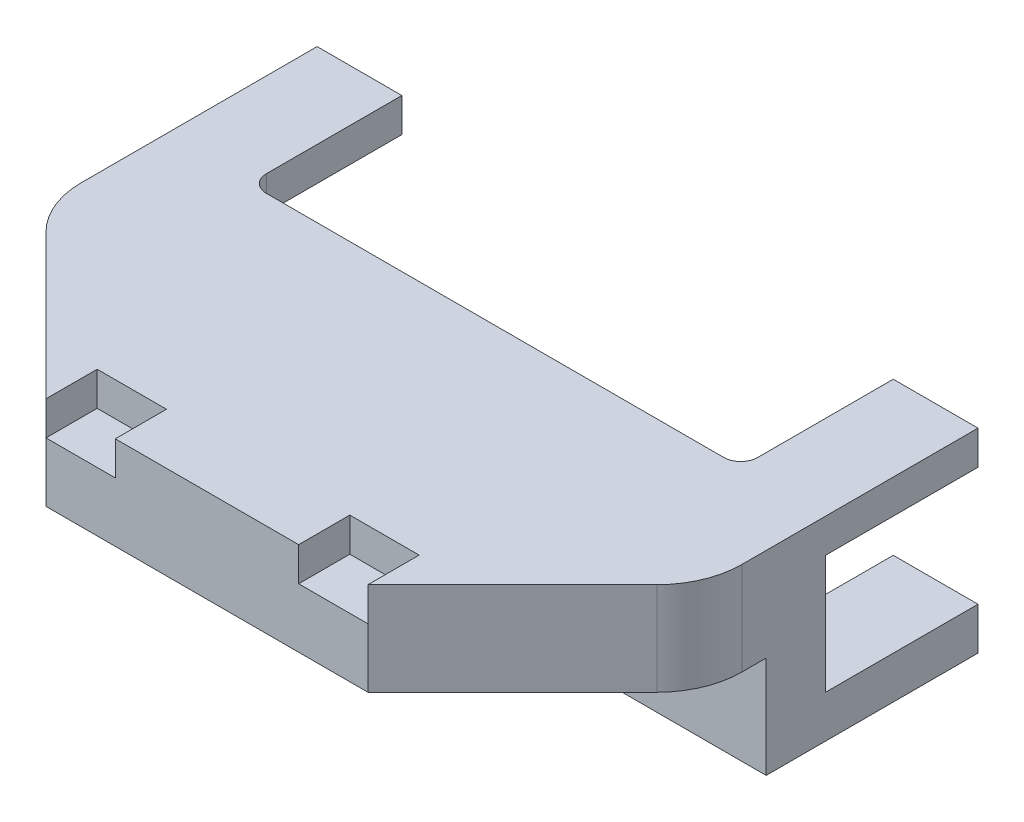
SolidWorks part; units mm, degrees
ref_plane "Front Plane" through (0, 0, 0) normal (0, 0, 1) x (1, 0, 0)
ref_plane "Top Plane" through (0, 0, 0) normal (0, 1, 0) x (1, 0, 0)
ref_plane "Right Plane" through (0, 0, 0) normal (1, 0, 0) x (0, 0, -1)
sketch "Sketch1" plane through (0, 0, 0) normal (0, 0, 1) x (1, 0, 0)
  line L1 (0, 0) -> (39, 0)
  line L2 (0, 0) -> (0, -11.5)
  line L3 (0, -11.5) -> (39, -11.5)
  line L4 (39, 0) -> (39, -11.5)
  dimension "D1" = 11.5
  dimension "D2" = 39
extrude "Boss-Extrude1" add sketch "Sketch1" along normal blind 17
sketch "Sketch2" plane through (0, 0, 0) normal (0, 0, -1) x (-1, 0, 0)
  line L1 (0, -11.5) -> (-5, -11.5)
  line L2 (0, -11.5) -> (0, -9)
  line L3 (0, -9) -> (-5, -9)
  line L4 (-5, -11.5) -> (-5, -9)
  line L5 (0, 0) -> (-5, 0)
  line L6 (0, 0) -> (0, -2)
  line L7 (0, -2) -> (-5, -2)
  line L8 (-5, 0) -> (-5, -2)
  line L9 (-39, -11.5) -> (-34, -11.5)
  line L10 (-39, -11.5) -> (-39, -9)
  line L11 (-39, -9) -> (-34, -9)
  line L12 (-34, -11.5) -> (-34, -9)
  line L13 (-39, 0) -> (-34, 0)
  line L14 (-39, 0) -> (-39, -2)
  line L15 (-39, -2) -> (-34, -2)
  line L16 (-34, 0) -> (-34, -2)
  dimension "D1" = 2.5
  dimension "D2" = 2
  dimension "D3" = 2.5
  dimension "D4" = 2
  dimension "D5" = 5
  dimension "D6" = 5
  dimension "D7" = 5
  dimension "D8" = 5
extrude "Boss-Extrude2" add sketch "Sketch2" along normal blind 9
fillet "Fillet3" radius 1 1 edges at (34, -1, 0)
fillet "Fillet4" radius 1 1 edges at (5, -1, 0)
fillet "Fillet5" radius 1 1 edges at (34, -10.25, 0)
fillet "Fillet6" radius 1 1 edges at (5, -10.25, 0)
chamfer "Chamfer1" distance 10 angle 45 1 edges at (39, -5.75, 17)
chamfer "Chamfer2" distance 10 angle 45 1 edges at (0, -5.75, 17)
sketch "Sketch4" plane through (0, 0, 0) normal (0, 1, 0) x (1, 0, 0)
  line L1 (29, -17) -> (24.91, -17)
  line L2 (29, -17) -> (29, -13.98)
  line L3 (29, -13.98) -> (24.91, -13.98)
  line L4 (24.91, -17) -> (24.91, -13.98)
  line L5 (10, -17) -> (14.09, -17)
  line L6 (10, -17) -> (10, -13.98)
  line L7 (10, -13.98) -> (14.09, -13.98)
  line L8 (14.09, -17) -> (14.09, -13.98)
  dimension "D1" = 4.09
  dimension "D2" = 3.02
  dimension "D3" = 3.02
  dimension "D4" = 4.09
extrude "Cut-Extrude1" cut sketch "Sketch4" against normal blind 2
sketch "Sketch5" plane through (0, -11.5, 0) normal (0, -1, 0) x (1, 0, 0)
  line L7 (0, 3.5) -> (45.2131, 3.5)
  line L8 (0, 3.5) -> (0, 25.1627)
  line L9 (0, 25.1627) -> (45.2131, 25.1627)
  line L10 (45.2131, 3.5) -> (45.2131, 25.1627)
  line L11 (6, 0) -> (33, 0) construction
  dimension "D1" = 3.5
extrude "Cut-Extrude2" cut sketch "Sketch5" against normal blind 6 contours L8 L7 L10 L9
fillet "Fillet7" radius 5 1 edges at (0, -2.75, 7)
fillet "Fillet8" radius 5 1 edges at (39, -2.75, 7)
